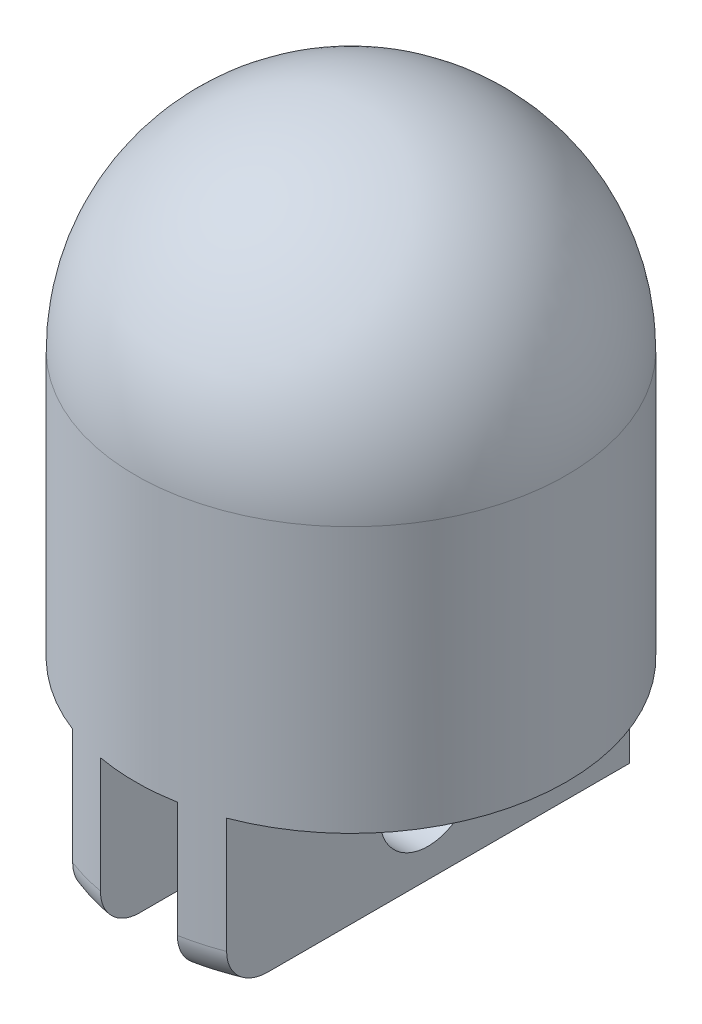
SolidWorks part; units mm, degrees
ref_plane "Front Plane" through (0, 0, 0) normal (0, 0, 1) x (1, 0, 0)
ref_plane "Top Plane" through (0, 0, 0) normal (0, 1, 0) x (1, 0, 0)
ref_plane "Right Plane" through (0, 0, 0) normal (1, 0, 0) x (0, 0, -1)
sketch "Sketch1" plane through (0, 0, 0) normal (0, 0, 1) x (1, 0, 0)
  line L0 (0, 0) -> (0, 5.6026)
  line L1 (0, 0) -> (-14.224, 0)
  line L2 (-14.224, 0) -> (-14.224, 27.686)
  line L6 (0, 5.6026) -> (-2.54, 5.6026)
  line L7 (-2.54, 22.86) -> (-2.54, 5.6026)
  line L8 (0, 33.1396) -> (0, 41.91)
  arc A0 (0, 41.91) -> (-14.224, 27.686) centre (0, 27.686) ccw
  arc A1 (-2.54, 22.86) -> (0, 33.1396) centre (0, 27.686) cw
  dimension "D3" = 28.448
  dimension "D1" = 41.91
  dimension "D2" = 14.224
  dimension "D4" = 2.54
revolve "Revolve1" add sketch "Sketch1" angle 360 about L0
sketch "Sketch2" plane through (0, 0, 0) normal (0, -1, 0) x (1, 0, 0)
  line L0 (-2.54, 13.9954) -> (-2.54, -13.9954)
  line L1 (-5.08, 13.2859) -> (-5.08, -13.2859)
  line L2 (2.54, 13.9954) -> (2.54, -13.9954)
  line L3 (5.08, 13.2859) -> (5.08, -13.2859)
  circle A0 centre (0, 0) radius 14.224 construction
  arc A1 (-5.08, 13.2859) -> (-5.08, -13.2859) centre (0, 0) ccw
  arc A2 (-2.54, -13.9954) -> (2.54, -13.9954) centre (0, 0) ccw
  arc A3 (5.08, -13.2859) -> (5.08, 13.2859) centre (0, 0) ccw
  arc A4 (2.54, 13.9954) -> (-2.54, 13.9954) centre (0, 0) ccw
  dimension "D1" = 2.54
  dimension "D2" = 2.54
  dimension "D3" = 2.54
  dimension "D4" = 2.54
extrude "Cut-Extrude1" cut sketch "Sketch2" against normal blind 10.16
sketch "Sketch3" plane through (-5.08, 0, 0) normal (-1, 0, 0) x (0, 0, 1)
  line L0 (0, -15.6464) -> (0, 15.6464) construction
  line L1 (-13.2859, 0) -> (13.2859, 0) construction
  circle A0 centre (0, 5.08) radius 3.175
  dimension "D2" = 6.35
  dimension "D1" = 5.08
extrude "Cut-Extrude2" cut sketch "Sketch3" against normal through all
fillet "Fillet1" radius 2.54 2 edges at (-3.8265, 0, 13.6996) (3.8265, 0, 13.6996)
